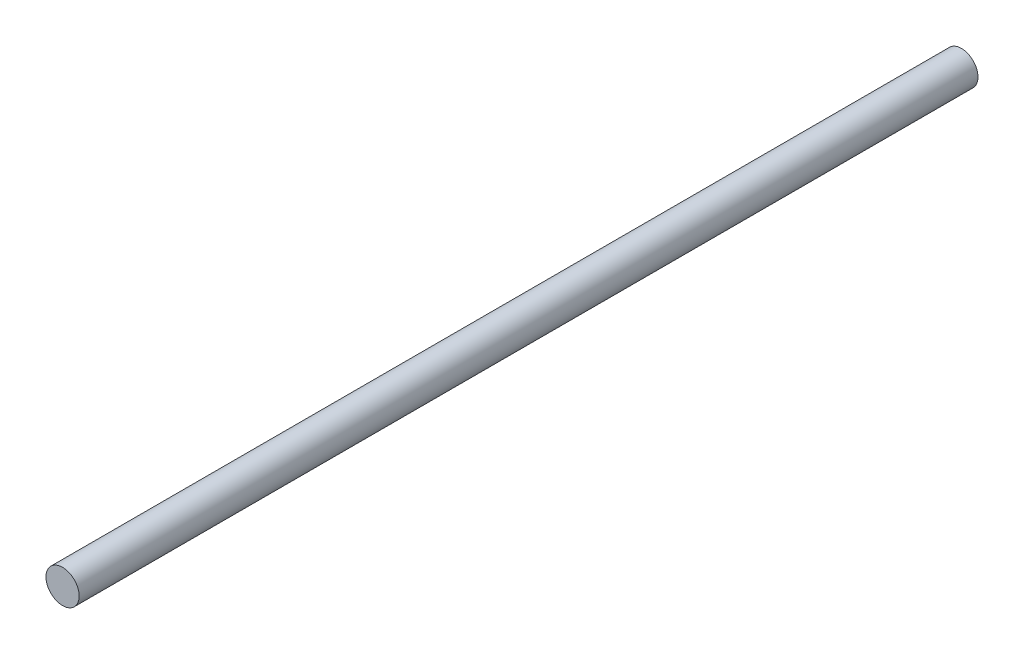
SolidWorks part; units mm, degrees
ref_plane "Front Plane" through (0, 0, 0) normal (0, 0, 1) x (1, 0, 0)
ref_plane "Top Plane" through (0, 0, 0) normal (0, 1, 0) x (1, 0, 0)
ref_plane "Right Plane" through (0, 0, 0) normal (1, 0, 0) x (0, 0, -1)
sketch "Sketch1" plane through (0, 0, 0) normal (0, 0, 1) x (1, 0, 0)
  circle A0 centre (0, 0) radius 5.9995
  dimension "D1" = 11.999
extrude "Boss-Extrude1" add sketch "Sketch1" along normal blind 325.0006
